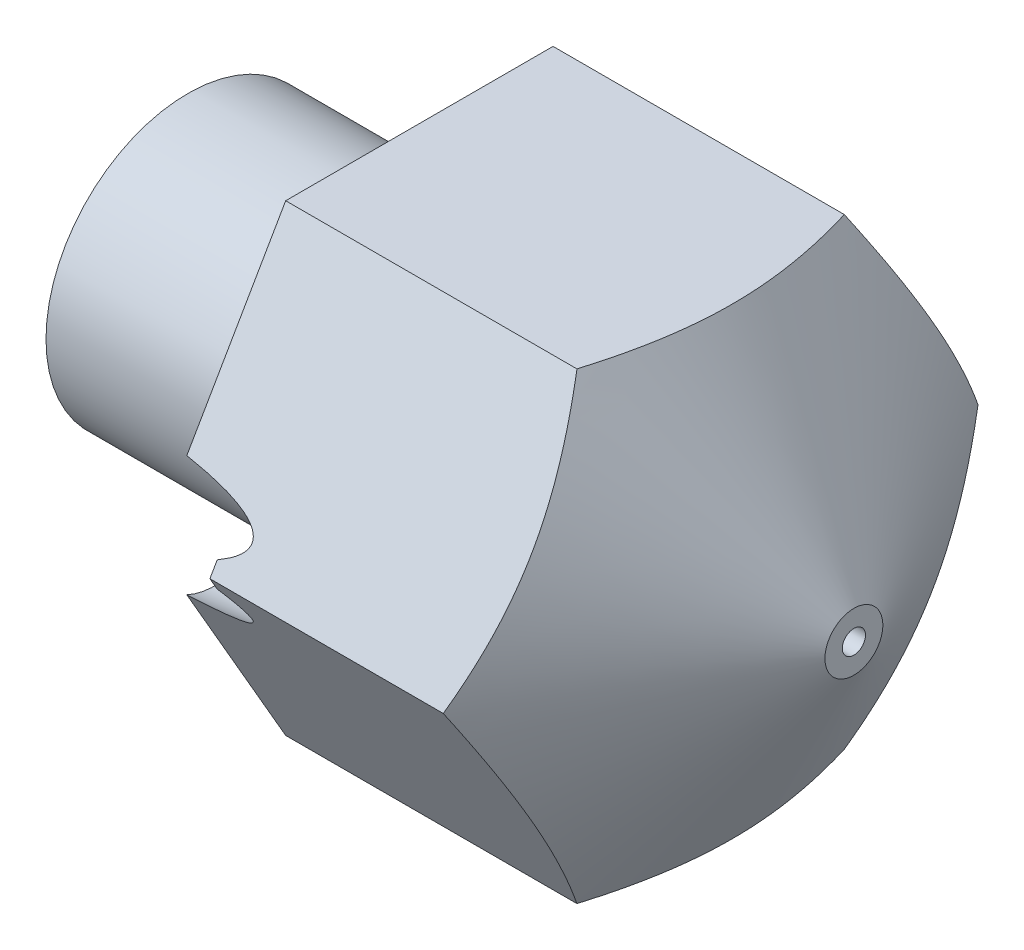
SolidWorks part; units mm, degrees
material "Brass"
ref_plane "Front Plane" through (0, 0, 0) normal (0, 0, 1) x (1, 0, 0)
ref_plane "Top Plane" through (0, 0, 0) normal (0, 1, 0) x (1, 0, 0)
ref_plane "Right Plane" through (0, 0, 0) normal (1, 0, 0) x (0, 0, -1)
sketch "Sketch1" plane through (0, 0, 0) normal (0, 0, 1) x (1, 0, 0)
  line L0 (-7.5065, 8) -> (-4.5065, 8)
  line L1 (0, 0.5) -> (-4.5065, 8)
  line L2 (0, 0.2) -> (-0.5, 0.2)
  line L3 (-0.9807, 1) -> (-8.5065, 1)
  line L4 (-0.5, 0.2) -> (-0.9807, 1)
  line L5 (-8.897, 1.65) -> (-11.5065, 1.65)
  line L6 (-7.5065, 2.45) -> (-7.5065, 8)
  line L7 (-8.5065, 1) -> (-8.897, 1.65)
  line L8 (0, 0.5) -> (0, 0.2)
  line L9 (-1000, 0) -> (49000, 0) construction
  line L10 (0, -1000) -> (0, 49000) construction
  line L12 (-11.5065, 1.65) -> (-11.5065, 2.45)
  line L13 (-11.5065, 2.45) -> (-7.5065, 2.45)
  dimension "D2" = 16
  dimension "D3" = 3
  dimension "D4" = 0.4
  dimension "D5" = 7.5065
  dimension "D6" = 59
  dimension "D7" = 7.0065
  dimension "D8" = 1
  dimension "D9" = 3
  dimension "D10" = 0.5831
  dimension "D11" = 0.5
  dimension "D12" = 2
  dimension "D13" = 3.3
  dimension "D14" = 4.9
  dimension "D15" = 4
  dimension "D16" = 7.5258
revolve "Revolve1" add sketch "Sketch1" angle 360 about L9
sketch "Sketch2" plane through (0, 0, 0) normal (1, 0, 0) x (0, 0, -1)
  line L1 (4.6188, 0) -> (2.3094, 4)
  line L2 (2.3094, 4) -> (-2.3094, 4)
  line L3 (-2.3094, 4) -> (-4.6188, 0)
  line L4 (-4.6188, 0) -> (-2.3094, -4)
  line L5 (-2.3094, -4) -> (2.3094, -4)
  line L6 (2.3094, -4) -> (4.6188, 0)
  circle A1 centre (0, 0) radius 4 construction
  dimension "D1" = 8
extrude "Cut-Extrude1" cut sketch "Sketch2" against normal through all flip side to cut
sketch "Sketch3" plane through (0, 0, 0) normal (0, 1, 0) x (1, 0, 0)
  line L0 (-10.3636, -4.0262) -> (-10.1639, -5.1588)
  line L1 (-10.1639, -5.1588) -> (-2.2854, -3.7696)
  line L2 (-2.2854, -3.7696) -> (-1.8046, -2.5171)
  line L3 (-1.8046, -2.5171) -> (-10.3636, -4.0262) construction
  line L4 (-10.3636, -4.0262) -> (-9.6988, -4.0262) construction
  line L5 (-1.8046, -2.5171) -> (-10.3636, -4.0262)
  line L6 (-7.2095, -4.6378) -> (-7.4092, -3.5053) construction
  dimension "D1" = 59
  dimension "D2" = 2.3
  dimension "D3" = 8
  dimension "D4" = 170
  dimension "D5" = 5
revolve "Cut-Revolve1" cut sketch "Sketch3" angle 360 about L5
sketch "Sketch4" plane through (-7.5065, 0, 0) normal (-1, 0, 0) x (0, 0, 1)
  line L1 (3.6188, 0.5) -> (4.6188, 0.5)
  line L2 (3.6188, 0.5) -> (3.6188, -0.5)
  line L3 (3.6188, -0.5) -> (4.6188, -0.5)
  line L4 (4.6188, 0.5) -> (4.6188, -0.5)
  dimension "D1" = 1
  dimension "D2" = 1
extrude "Cut-Extrude2" cut sketch "Sketch4" against normal blind 1
